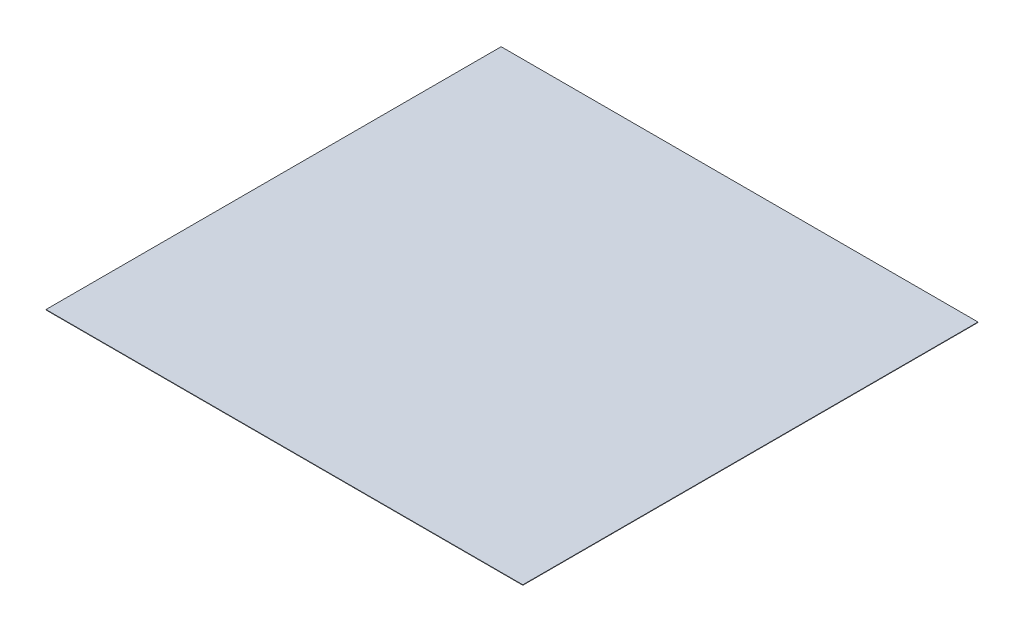
SolidWorks part; units mm, degrees
ref_plane "Front Plane" through (0, 0, 0) normal (0, 0, 1) x (1, 0, 0)
ref_plane "Top Plane" through (0, 0, 0) normal (0, 1, 0) x (1, 0, 0)
ref_plane "Right Plane" through (0, 0, 0) normal (1, 0, 0) x (0, 0, -1)
sketch "Sketch1" plane through (0, 0, 0) normal (0, 1, 0) x (1, 0, 0)
  line L1 (110, -105) -> (-110, -105)
  line L2 (110, -105) -> (110, 105)
  line L3 (110, 105) -> (-110, 105)
  line L4 (-110, -105) -> (-110, 105)
  line L5 (110, -105) -> (-110, 105) construction
  line L6 (110, 105) -> (-110, -105) construction
  point P0 (0, 0)
  dimension "D1" = 220
  dimension "D2" = 210
extrude "Boss-Extrude1" add sketch "Sketch1" along normal blind 0.2
